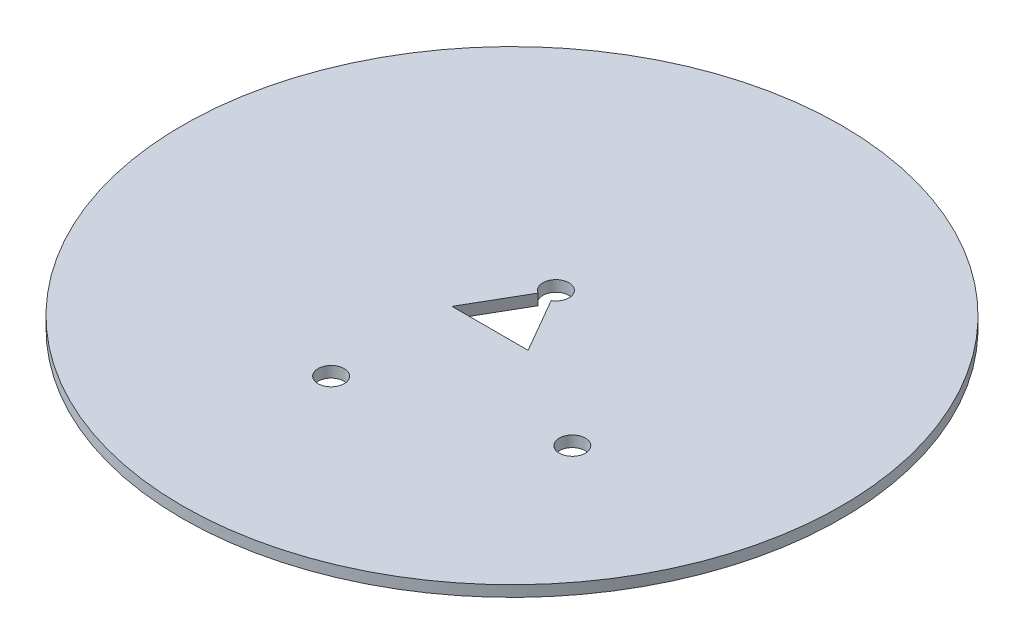
SolidWorks part; units mm, degrees
ref_plane "Plan de face" through (0, 0, 0) normal (0, 0, 1) x (1, 0, 0)
ref_plane "Plan de dessus" through (0, 0, 0) normal (0, 1, 0) x (1, 0, 0)
ref_plane "Plan de droite" through (0, 0, 0) normal (1, 0, 0) x (0, 0, -1)
sketch "Esquisse1" plane through (0, 0, 0) normal (0, 1, 0) x (1, 0, 0)
  line L1 (0, 40) -> (-34.641, -20)
  line L2 (-34.641, -20) -> (34.641, -20)
  line L3 (34.641, -20) -> (0, 40)
  circle A0 centre (0, 0) radius 300
  circle A1 centre (0, 0) radius 40 construction
  circle A2 centre (0, 40) radius 11.9028
  circle A3 centre (129.9038, -75) radius 11.9028
  circle A4 centre (-34.641, -130) radius 11.9028
  point P4 (0, 0)
  point P9 (0, 0)
  point P14 (31.7543, -55)
  dimension "D1" = 600
  dimension "D2" = 80
  dimension "D3" = 3
extrude "Boss.-Extru.1" add sketch "Esquisse1" along normal blind 10 contours A0 L3 L2 L1
sketch "Esquisse2" plane through (0, 0, 0) normal (1, 0, 0) x (0, 0, -1)
  line L0 (0, 0) -> (0, 57.6957) construction
  line L2 (300, 0) -> (-300, 0)
  line L3 (300, 0) -> (-300, 0)
  dimension "D1" = 0
equation "\"Rb\" = 80mm"
equation "\"D2@Esquisse1\"=\"Rb\""
